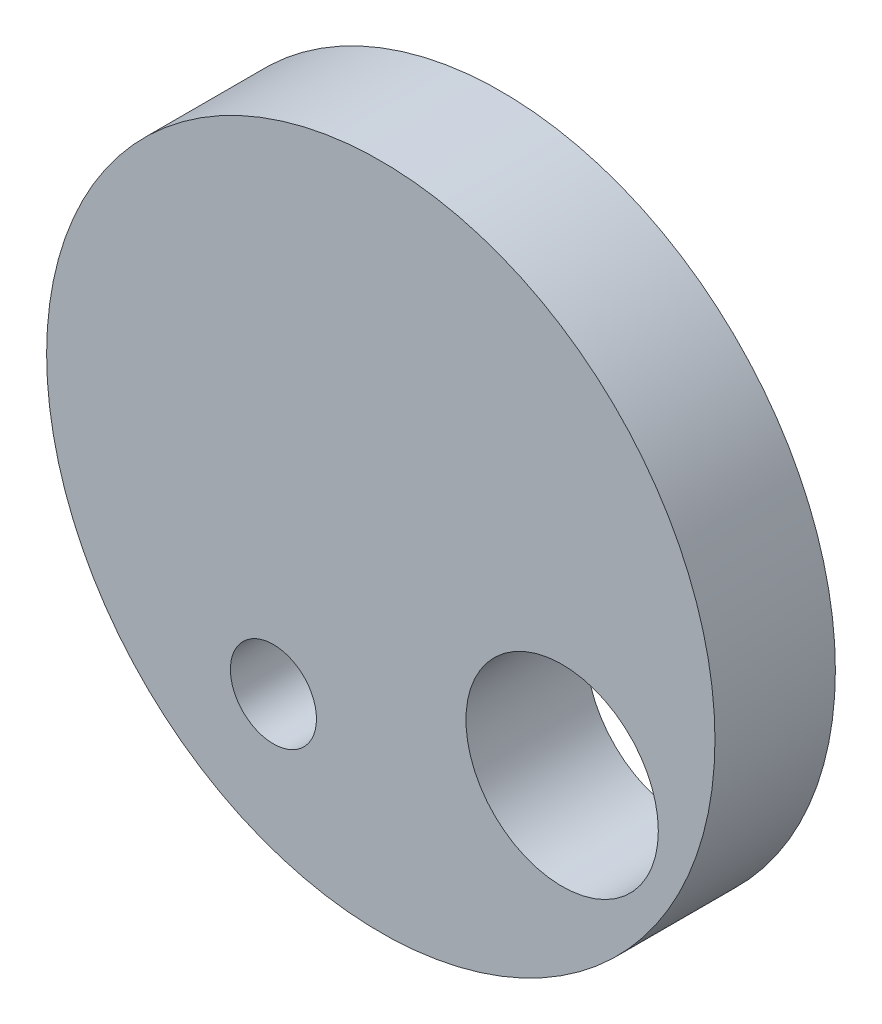
SolidWorks part; units mm, degrees
ref_plane "Alzado" through (0, 0, 0) normal (0, 0, 1) x (1, 0, 0)
ref_plane "Planta" through (0, 0, 0) normal (0, 1, 0) x (1, 0, 0)
ref_plane "Vista lateral" through (0, 0, 0) normal (1, 0, 0) x (0, 0, -1)
sketch "Croquis1" plane through (0, 0, 0) normal (0, 0, 1) x (1, 0, 0)
  line L0 (-17.8302, -30.1178) -> (0, 0) construction
  line L1 (0, 0) -> (30.1178, -17.8302) construction
  circle A0 centre (0, 0) radius 55.5
  circle A2 centre (0, 0) radius 35 construction
  circle A3 centre (-17.8302, -30.1178) radius 7.1498
  circle A4 centre (30.1178, -17.8302) radius 15.976
  dimension "D1" = 111
  dimension "D2" = 70
  dimension "D3" = 90
extrude "Saliente-Extruir1" add sketch "Croquis1" along normal blind 20
